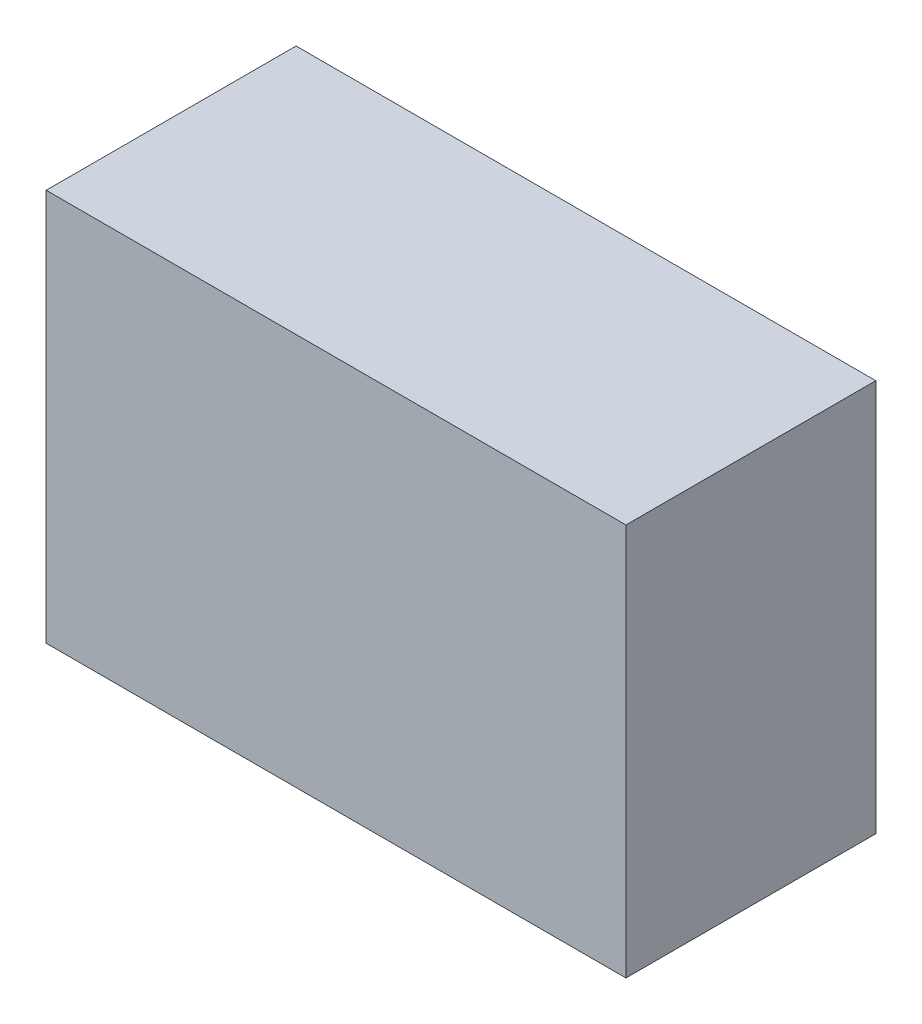
SolidWorks part; units mm, degrees
ref_plane "Front Plane" through (0, 0, 0) normal (0, 0, 1) x (1, 0, 0)
ref_plane "Top Plane" through (0, 0, 0) normal (0, 1, 0) x (1, 0, 0)
ref_plane "Right Plane" through (0, 0, 0) normal (1, 0, 0) x (0, 0, -1)
other "Configuration Table"
sketch "Sketch1" plane through (0, 0, 0) normal (0, 1, 0) x (1, 0, 0)
  line L1 (-75.438, -32.512) -> (75.438, -32.512)
  line L2 (-75.438, -32.512) -> (-75.438, 32.512)
  line L3 (-75.438, 32.512) -> (75.438, 32.512)
  line L4 (75.438, -32.512) -> (75.438, 32.512)
  line L5 (-75.438, -32.512) -> (75.438, 32.512) construction
  line L6 (-75.438, 32.512) -> (75.438, -32.512) construction
  point P0 (0, 0)
  dimension "D1" = 65.024
  dimension "D2" = 150.876
extrude "Boss-Extrude1" add sketch "Sketch1" along normal blind 102.108
